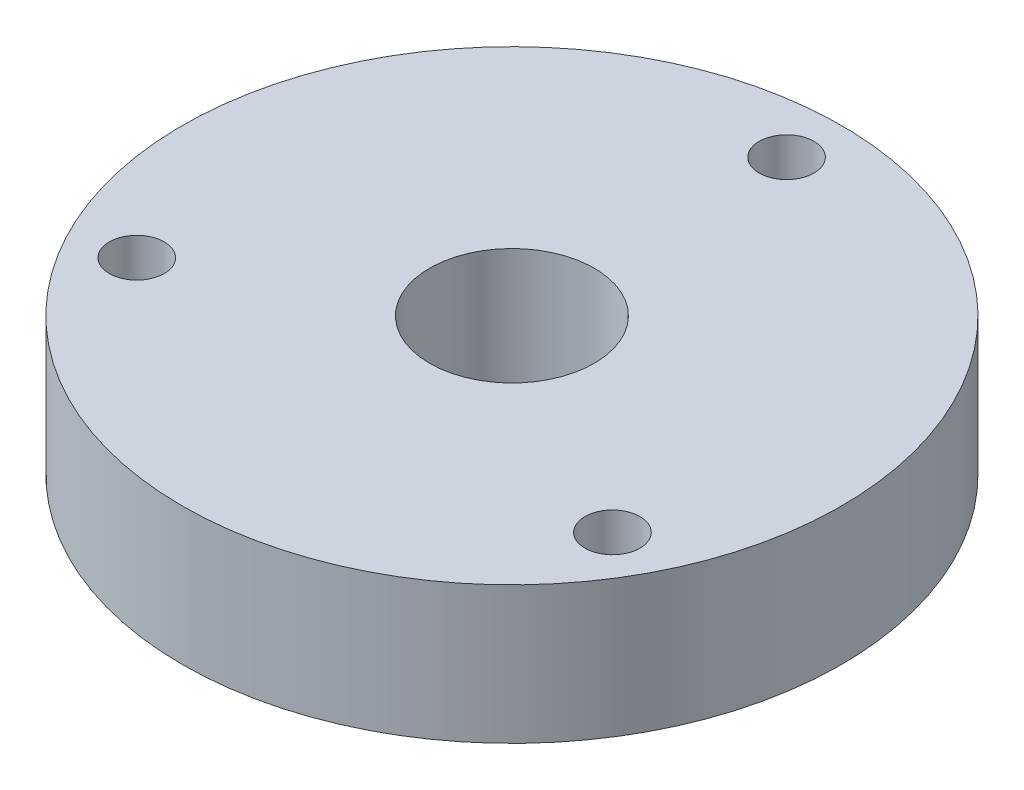
SolidWorks part; units mm, degrees
ref_plane "Front Plane" through (0, 0, 0) normal (0, 0, 1) x (1, 0, 0)
ref_plane "Top Plane" through (0, 0, 0) normal (0, 1, 0) x (1, 0, 0)
ref_plane "Right Plane" through (0, 0, 0) normal (1, 0, 0) x (0, 0, -1)
sketch "Sketch1" plane through (0, 0, 0) normal (0, 1, 0) x (1, 0, 0)
  line L0 (0, 0) -> (0, 10) construction
  circle A0 centre (0, 0) radius 12
  circle A1 centre (0, 10) radius 1
  circle A2 centre (0, 0) radius 3
  circle A3 centre (8.6603, -5) radius 1
  circle A4 centre (-8.6603, -5) radius 1
  point P7 (-10.0855, -2.5901)
  point P8 (0, 0)
  point P12 (0, 0)
  dimension "D1" = 24
  dimension "D2" = 6
  dimension "D3" = 2
  dimension "D4" = 10
  dimension "D5" = 3
extrude "Boss-Extrude1" add sketch "Sketch1" along normal blind 5
